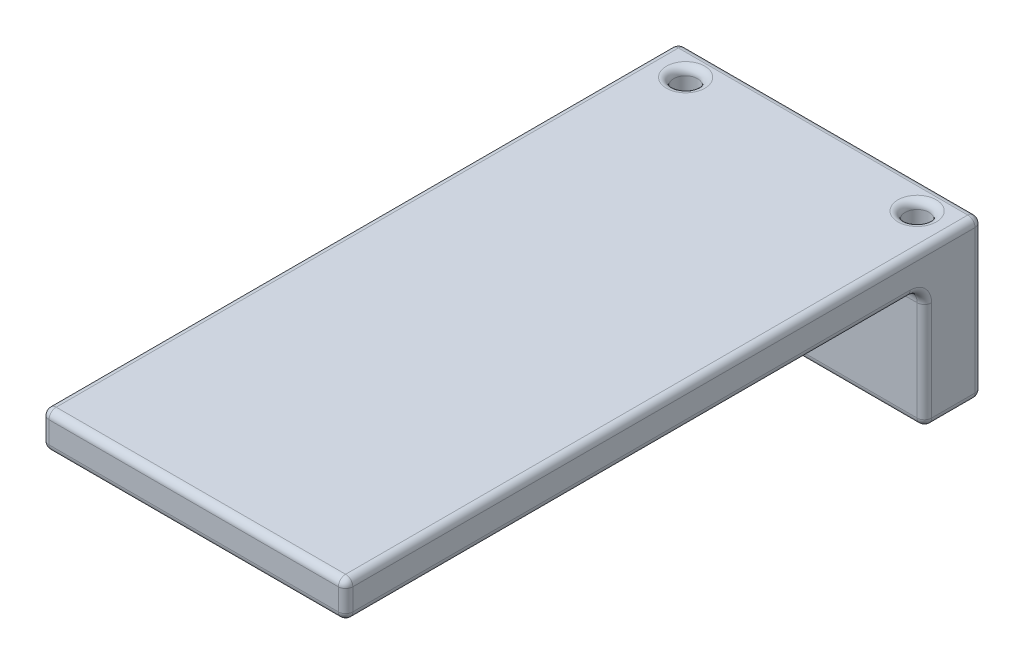
SolidWorks part; units mm, degrees
ref_plane "Front Plane" through (0, 0, 0) normal (0, 0, 1) x (1, 0, 0)
ref_plane "Top Plane" through (0, 0, 0) normal (0, 1, 0) x (1, 0, 0)
ref_plane "Right Plane" through (0, 0, 0) normal (1, 0, 0) x (0, 0, -1)
sketch "Sketch1" plane through (0, 0, 0) normal (0, 1, 0) x (1, 0, 0)
  line L1 (-21, -40) -> (21, -40)
  line L2 (-21, -40) -> (-21, 40)
  line L3 (-21, 40) -> (21, 40)
  line L4 (21, -40) -> (21, 40)
  line L5 (-21, -40) -> (21, 40) construction
  line L6 (-21, 40) -> (21, -40) construction
  point P0 (0, 0)
  dimension "D1" = 42
  dimension "D2" = 80
extrude "Boss-Extrude1" add sketch "Sketch1" along normal blind 5
sketch "Sketch2" plane through (0, 5, 0) normal (0, 1, 0) x (1, 0, 0)
  line L0 (21, -40) -> (21, 40) construction
  line L1 (-21, 40) -> (21, 40)
  line L2 (-21, 40) -> (-21, 48)
  line L3 (-21, 48) -> (21, 48)
  line L4 (21, 40) -> (21, 48)
  circle A0 centre (16, 44) radius 1.4 construction
  circle A1 centre (-16, 44) radius 1.4 construction
  circle A2 centre (16, 44) radius 1.4 construction
  circle A3 centre (-16, 44) radius 1.4 construction
  circle A4 centre (16, 44) radius 1.65
  circle A5 centre (-16, 44) radius 1.65
  dimension "D2" = 3.3
  dimension "D1" = 8
extrude "Boss-Extrude2" add sketch "Sketch2" against normal up to surface (21.8 mm away)
fillet "Fillet1" radius 2 1 edges at (0, 0, -40)
fillet "Fillet2" radius 1 23 edges at (-21, -9.4, -40) (-21, -0.5858, -39.4142) (0, -16.8, -48) (0, 5, -48) (-21, -5.9, -48) (21, 5, -4) (21, -5.9, -48) (21, -9.4, -40) (21, -0.5858, -39.4142) (16, -16.8, -42.35) (-16, -16.8, -42.35) (0, -16.8, -40) (21, -16.8, -44) (-21, -16.8, -44) (21, 0, 1) (-21, 0, 1) (-21, 2.5, 40) (0, 5, 40) (21, 2.5, 40) (0, 0, 40) (-21, 5, -4) (16, 5, -42.35) (-16, 5, -42.35)
